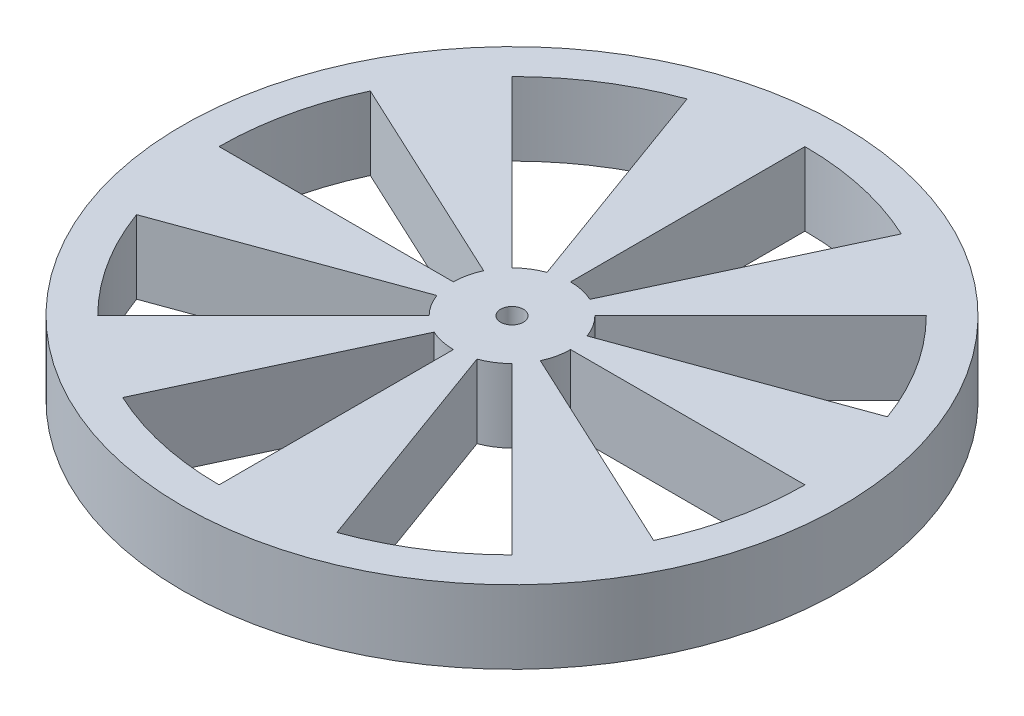
SolidWorks part; units mm, degrees
ref_plane "Front Plane" through (0, 0, 0) normal (0, 0, 1) x (1, 0, 0)
ref_plane "Top Plane" through (0, 0, 0) normal (0, 1, 0) x (1, 0, 0)
ref_plane "Right Plane" through (0, 0, 0) normal (1, 0, 0) x (0, 0, -1)
sketch "Sketch1" plane through (0, 0, 0) normal (0, 1, 0) x (1, 0, 0)
  line L0 (0, 40) -> (0, 8)
  line L1 (0, 0) -> (0.6551, 1.4048)
  line L2 (28.2843, 28.2843) -> (5.6569, 5.6569)
  line L3 (0, 0) -> (1.4565, 0.5301)
  line L4 (40, 0) -> (8, 0)
  line L5 (0, 0) -> (1.4048, -0.6551)
  line L6 (28.2843, -28.2843) -> (5.6569, -5.6569)
  line L7 (0, 0) -> (0.5301, -1.4565)
  line L8 (0, -40) -> (0, -8)
  line L9 (0, 0) -> (-0.6551, -1.4048)
  line L10 (-28.2843, -28.2843) -> (-5.6569, -5.6569)
  line L11 (0, 0) -> (-1.4565, -0.5301)
  line L12 (-40, 0) -> (-8, 0)
  line L13 (0, 0) -> (-1.4048, 0.6551)
  line L14 (-28.2843, 28.2843) -> (-5.6569, 5.6569)
  line L15 (0, 0) -> (-0.5301, 1.4565)
  line L16 (0, 1.55) -> (0, 0)
  line L17 (-2.7362, 7.5175) -> (-13.6808, 37.5877)
  line L18 (-1.096, 1.096) -> (0, 0)
  line L19 (-7.2505, 3.3809) -> (-36.2523, 16.9047)
  line L20 (-1.55, 0) -> (0, 0)
  line L21 (-7.5175, -2.7362) -> (-37.5877, -13.6808)
  line L22 (-1.096, -1.096) -> (0, 0)
  line L23 (-3.3809, -7.2505) -> (-16.9047, -36.2523)
  line L24 (0, -1.55) -> (0, 0)
  line L25 (2.7362, -7.5175) -> (13.6808, -37.5877)
  line L26 (1.096, -1.096) -> (0, 0)
  line L27 (7.2505, -3.3809) -> (36.2523, -16.9047)
  line L28 (1.55, 0) -> (0, 0)
  line L29 (7.5175, 2.7362) -> (37.5877, 13.6808)
  line L30 (1.096, 1.096) -> (0, 0)
  line L31 (3.3809, 7.2505) -> (16.9047, 36.2523)
  circle A0 centre (0, 0) radius 1.55
  circle A1 centre (0, 0) radius 45
  circle A2 centre (0, 0) radius 8
  arc A3 (-13.6808, 37.5877) -> (-28.2843, 28.2843) centre (0, 0) ccw
  arc A4 (-36.2523, 16.9047) -> (-40, 0) centre (0, 0) ccw
  arc A5 (-37.5877, -13.6808) -> (-28.2843, -28.2843) centre (0, 0) ccw
  arc A6 (-16.9047, -36.2523) -> (0, -40) centre (0, 0) ccw
  arc A7 (13.6808, -37.5877) -> (28.2843, -28.2843) centre (0, 0) ccw
  arc A8 (36.2523, -16.9047) -> (40, 0) centre (0, 0) ccw
  arc A9 (37.5877, 13.6808) -> (28.2843, 28.2843) centre (0, 0) ccw
  arc A10 (16.9047, 36.2523) -> (0, 40) centre (0, 0) ccw
  point P24 (0, 0)
  dimension "D1" = 3.1
  dimension "D2" = 25
  dimension "D3" = 8
extrude "Boss-Extrude1" add sketch "Sketch1" along normal blind 10 contours A1 A10 L31 A2 L2 A9 L29 L4 A8 L27 L6 A7 L25 L8 A6 L23 L10 A5 L21 L12 A4 L19 L14 A3 L17 L0 | A2 A0
